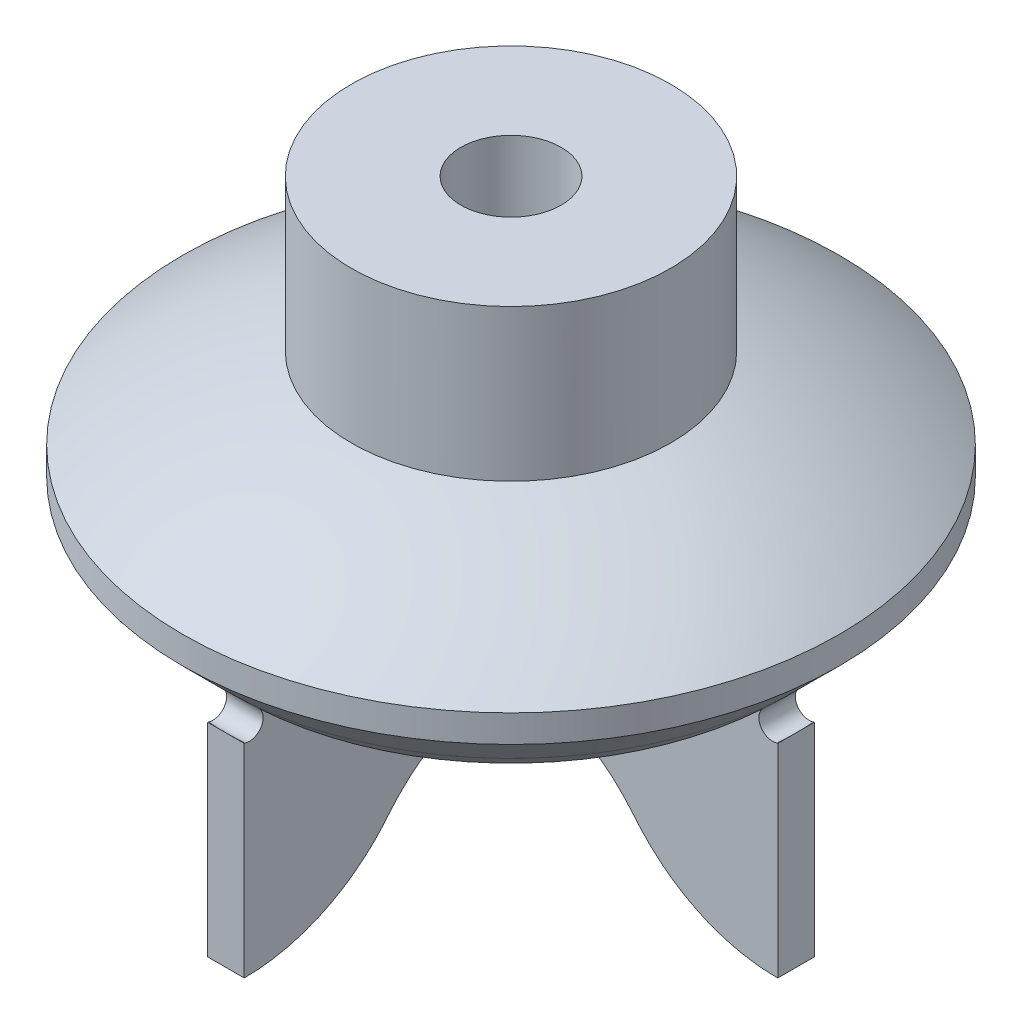
SolidWorks part; units mm, degrees
ref_plane "Front Plane" through (0, 0, 0) normal (0, 0, 1) x (1, 0, 0)
ref_plane "Top Plane" through (0, 0, 0) normal (0, 1, 0) x (1, 0, 0)
ref_plane "Right Plane" through (0, 0, 0) normal (1, 0, 0) x (0, 0, -1)
sketch "Sketch1" plane through (0, 0, 0) normal (0, 0, 1) x (1, 0, 0)
  line L0 (0, 0) -> (0, 119) construction
  line L2 (11, 119) -> (11, 103)
  line L3 (11, 103) -> (20, 103)
  line L4 (20, 103) -> (20, 84)
  line L5 (20, 84) -> (0, 84)
  line L7 (11, 119) -> (35, 119)
  line L8 (35, 119) -> (35, 85.8188)
  line L10 (72, 68) -> (72, 62)
  line L14 (0, 84) -> (0, 61.8056)
  line L15 (59.5, 49.5) -> (72, 62)
  arc A3 (-72, 68) -> (72, 68) centre (0, -34.1812) cw
  arc A4 (59.5, 49.5) -> (-59.5, 49.5) centre (0, -88.1944) ccw
  point P9 (0, 90.8188)
  point P14 (72, 68.0793)
  point P15 (0, 0)
  point P18 (0, 0)
  point P20 (72.0982, 62.2926)
  point P23 (0, 61.8056)
  dimension "D8" = 22
  dimension "D10" = 144
  dimension "D12" = 45
  dimension "D13" = 119
  dimension "D5" = 125
  dimension "D11" = 150
  dimension "D1" = 119
  dimension "D2" = 22
  dimension "D3" = 40
  dimension "D4" = 70
  dimension "D6" = 16
  dimension "D7" = 19
  dimension "D9" = 6
revolve "Revolve2" add sketch "Sketch1" angle 360 about L0
sketch "Sketch3" plane through (0, 0, 0) normal (0, 1, 0) x (1, 0, 0)
  line L0 (0, 0) -> (0, 7.1902) construction
  line L1 (4, -62.5) -> (-4, -62.5)
  line L2 (4, -62.5) -> (4, -4)
  line L3 (4, 62.5) -> (-4, 62.5)
  line L4 (-4, -62.5) -> (-4, -4)
  line L5 (0, 0) -> (-6.6247, 0) construction
  line L7 (-62.5, -4) -> (-4, -4)
  line L8 (-62.5, -4) -> (-62.5, 4)
  line L9 (-62.5, 4) -> (-4, 4)
  line L10 (62.5, -4) -> (62.5, 4)
  line L11 (4, -4) -> (62.5, -4)
  line L15 (4, 4) -> (62.5, 4)
  line L16 (4, 4) -> (4, 62.5)
  line L19 (-4, 4) -> (-4, 62.5)
  point P0 (0, 0)
  point P6 (0, 0)
  dimension "D1" = 8
  dimension "D2" = 8
  dimension "D3" = 8
  dimension "D4" = 125
  dimension "D5" = 125
extrude "Boss-Extrude3" add sketch "Sketch3" along normal up to next contours L11 L10 L15 L16 L3 L19 L9 L8 L7 L4 L1 L2
sketch "Sketch4" plane through (0, 0, 0) normal (0, 0, 1) x (1, 0, 0)
  line L3 (0, 0) -> (0, 38.0932) construction
  line L4 (62.5, 52.6279) -> (62.5, 0) construction
  line L6 (0, 30.0625) -> (0, 0)
  line L7 (62.5, 52.6279) -> (62.5, 44.5534) construction
  line L8 (0, 0) -> (-62.5, 0)
  line L9 (59.3654, 49.5) -> (4, 49.5) construction
  line L10 (62.5, 44.5534) -> (62.9839, 44.5534)
  line L11 (62.9839, 44.5534) -> (62.9839, 53.1118)
  line L12 (62.9839, 53.1118) -> (62.5, 52.6279)
  line L15 (62.5, 52.5) -> (72, 62) construction
  line L16 (-62.5, 52.6279) -> (-62.5, 0) construction
  arc A1 (59.3654, 49.5) -> (62.5, 44.5534) centre (61.4843, 47.3763) ccw
  arc A2 (-62.5, 0) -> (-31.25, 15.0313) centre (-62.5, 40) ccw
  arc A3 (-31.25, 15.0313) -> (0, 30.0625) centre (0, -9.9375) cw
  spline S1 degree 3 poles (1850.9677, 761.123) (-65.3711, 1023.7894) (214.3523, -916.4659) (-1745.6968, -609.9526) knots -398.986426 -398.986426 -398.986426 -398.986426 394.821446 394.821446 394.821446 394.821446 only from (62.5, 52.6279) to (59.3654, 49.5) construction
  spline S2 degree 3 poles (62.5, 52.6279) (61.4552, 51.5852) (60.4103, 50.5426) (59.3654, 49.5) knots 0 0 0 0 1 1 1 1
  dimension "D1" = 3
  dimension "D2" = 40
revolve "Cut-Revolve5" cut sketch "Sketch4" angle 360 about L3
